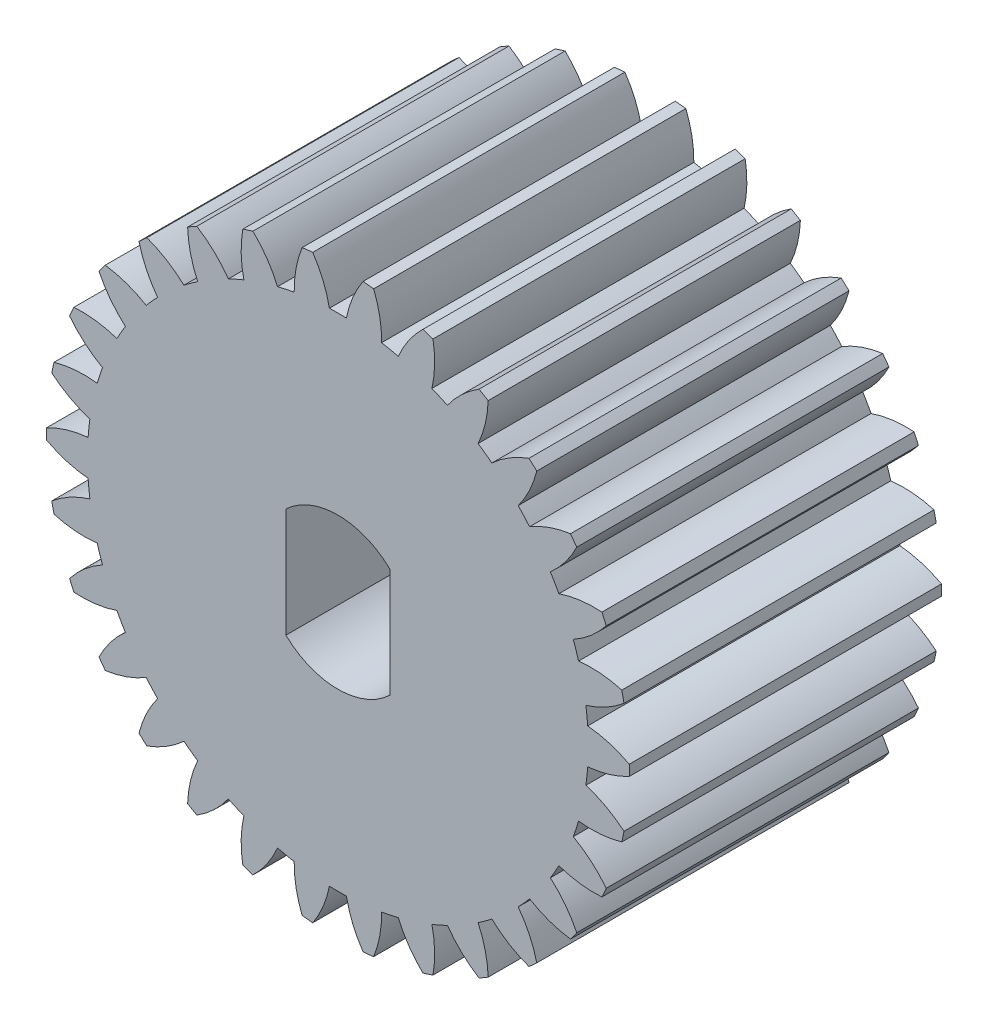
SolidWorks part; units mm, degrees
material "ABS"
ref_plane "Alzado" through (0, 0, 0) normal (0, 0, 1) x (1, 0, 0)
ref_plane "Planta" through (0, 0, 0) normal (0, 1, 0) x (1, 0, 0)
ref_plane "Vista lateral" through (0, 0, 0) normal (1, 0, 0) x (0, 0, -1)
sketch "Croquis1" plane through (0, 0, 0) normal (0, 0, 1) x (1, 0, 0)
  line L0 (-162.0016, 37.1002) -> (-162.0016, 32.9002)
  line L3 (-160.0016, 35.0002) -> (-160.0016, 39.913) construction
  line L4 (-158.0016, 37.1002) -> (-158.0016, 32.9002)
  arc A122 (-171.1997, 34.7961) -> (-169.6015, 34.3201) centre (-169.2256, 38.5032) ccw
  arc A123 (-169.6015, 34.3201) -> (-169.5331, 33.6695) centre (-160.0016, 35.0002) ccw
  arc A124 (-169.5331, 33.6695) -> (-170.9974, 32.8716) centre (-168.2957, 29.656) ccw
  arc A125 (-170.9974, 32.8716) -> (-170.9126, 32.4723) centre (-160.0016, 35.0002) ccw
  arc A126 (-170.9126, 32.4723) -> (-169.2503, 32.339) centre (-169.7523, 36.5089) ccw
  arc A127 (-169.2503, 32.339) -> (-169.0482, 31.7169) centre (-160.0016, 35.0002) ccw
  arc A128 (-169.0482, 31.7169) -> (-170.3146, 30.632) centre (-167.0033, 28.0483) ccw
  arc A129 (-170.3146, 30.632) -> (-170.1486, 30.2591) centre (-160.0016, 35.0002) ccw
  arc A130 (-170.1486, 30.2591) -> (-168.4949, 30.4742) centre (-169.8529, 34.4486) ccw
  arc A131 (-168.4949, 30.4742) -> (-168.1679, 29.9077) centre (-160.0016, 35.0002) ccw
  arc A132 (-168.1679, 29.9077) -> (-169.181, 28.5832) centre (-165.4049, 26.7445) ccw
  arc A133 (-169.181, 28.5832) -> (-168.9411, 28.253) centre (-160.0016, 35.0002) ccw
  arc A134 (-168.9411, 28.253) -> (-167.3683, 28.8073) centre (-169.523, 32.4125) ccw
  arc A135 (-167.3683, 28.8073) -> (-166.9306, 28.3212) centre (-160.0016, 35.0002) ccw
  arc A136 (-166.9306, 28.3212) -> (-167.6463, 26.815) centre (-163.5704, 25.8015) ccw
  arc A137 (-167.6463, 26.815) -> (-167.3429, 26.5418) centre (-160.0016, 35.0002) ccw
  arc A138 (-167.3429, 26.5418) -> (-165.9197, 27.411) centre (-168.7769, 30.4894) ccw
  arc A139 (-165.9197, 27.411) -> (-165.3905, 27.0265) centre (-160.0016, 35.0002) ccw
  arc A140 (-165.3905, 27.0265) -> (-165.7774, 25.4044) centre (-161.5799, 25.2605) ccw
  arc A141 (-165.7774, 25.4044) -> (-165.4239, 25.2003) centre (-160.0016, 35.0002) ccw
  arc A142 (-165.4239, 25.2003) -> (-164.2125, 26.3464) centre (-167.6473, 28.7635) ccw
  arc A143 (-164.2125, 26.3464) -> (-163.615, 26.0803) centre (-160.0016, 35.0002) ccw
  arc A144 (-163.615, 26.0803) -> (-163.6561, 24.4132) centre (-159.5204, 25.1452) ccw
  arc A145 (-163.6561, 24.4132) -> (-163.2679, 24.2871) centre (-160.0016, 35.0002) ccw
  arc A146 (-163.2679, 24.2871) -> (-162.3213, 25.66) centre (-166.1835, 27.3102) ccw
  arc A147 (-162.3213, 25.66) -> (-161.6814, 25.524) centre (-160.0016, 35.0002) ccw
  arc A148 (-161.6814, 25.524) -> (-161.3751, 23.8848) centre (-157.4819, 25.4606) ccw
  arc A149 (-161.3751, 23.8848) -> (-160.9691, 23.8421) centre (-160.0016, 35.0002) ccw
  arc A150 (-160.9691, 23.8421) -> (-160.3286, 25.3818) centre (-164.4496, 26.1929) ccw
  arc A151 (-160.3286, 25.3818) -> (-159.6745, 25.3818) centre (-160.0016, 35.0002) ccw
  arc A152 (-159.6745, 25.3818) -> (-159.034, 23.8421) centre (-155.5536, 26.1929) ccw
  arc A153 (-159.034, 23.8421) -> (-158.6281, 23.8848) centre (-160.0016, 35.0002) ccw
  arc A154 (-158.6281, 23.8848) -> (-158.3217, 25.524) centre (-162.5212, 25.4606) ccw
  arc A155 (-158.3217, 25.524) -> (-157.6819, 25.66) centre (-160.0016, 35.0002) ccw
  arc A156 (-157.6819, 25.66) -> (-156.7353, 24.2871) centre (-153.8196, 27.3102) ccw
  arc A157 (-156.7353, 24.2871) -> (-156.347, 24.4132) centre (-160.0016, 35.0002) ccw
  arc A158 (-156.347, 24.4132) -> (-156.3882, 26.0803) centre (-160.4828, 25.1452) ccw
  arc A159 (-156.3882, 26.0803) -> (-155.7906, 26.3464) centre (-160.0016, 35.0002) ccw
  arc A160 (-155.7906, 26.3464) -> (-154.5793, 25.2003) centre (-152.3559, 28.7635) ccw
  arc A161 (-154.5793, 25.2003) -> (-154.2257, 25.4044) centre (-160.0016, 35.0002) ccw
  arc A162 (-154.2257, 25.4044) -> (-154.6126, 27.0265) centre (-158.4233, 25.2605) ccw
  arc A163 (-154.6126, 27.0265) -> (-154.0834, 27.411) centre (-160.0016, 35.0002) ccw
  arc A164 (-154.0834, 27.411) -> (-152.6602, 26.5418) centre (-151.2263, 30.4894) ccw
  arc A165 (-152.6602, 26.5418) -> (-152.3569, 26.815) centre (-160.0016, 35.0002) ccw
  arc A166 (-152.3569, 26.815) -> (-153.0725, 28.3212) centre (-156.4328, 25.8015) ccw
  arc A167 (-153.0725, 28.3212) -> (-152.6348, 28.8073) centre (-160.0016, 35.0002) ccw
  arc A168 (-152.6348, 28.8073) -> (-151.0621, 28.253) centre (-150.4802, 32.4125) ccw
  arc A169 (-151.0621, 28.253) -> (-150.8221, 28.5832) centre (-160.0016, 35.0002) ccw
  arc A170 (-150.8221, 28.5832) -> (-151.8353, 29.9077) centre (-154.5982, 26.7445) ccw
  arc A171 (-151.8353, 29.9077) -> (-151.5082, 30.4742) centre (-160.0016, 35.0002) ccw
  arc A172 (-151.5082, 30.4742) -> (-149.8546, 30.2591) centre (-150.1502, 34.4486) ccw
  arc A173 (-149.8546, 30.2591) -> (-149.6885, 30.632) centre (-160.0016, 35.0002) ccw
  arc A174 (-149.6885, 30.632) -> (-150.955, 31.7169) centre (-152.9998, 28.0483) ccw
  arc A175 (-150.955, 31.7169) -> (-150.7528, 32.339) centre (-160.0016, 35.0002) ccw
  arc A176 (-150.7528, 32.339) -> (-149.0906, 32.4723) centre (-150.2508, 36.5089) ccw
  arc A177 (-149.0906, 32.4723) -> (-149.0057, 32.8716) centre (-160.0016, 35.0002) ccw
  arc A178 (-149.0057, 32.8716) -> (-150.47, 33.6695) centre (-151.7075, 29.656) ccw
  arc A179 (-150.47, 33.6695) -> (-150.4016, 34.3201) centre (-160.0016, 35.0002) ccw
  arc A180 (-150.4016, 34.3201) -> (-148.8034, 34.7961) centre (-150.7776, 38.5032) ccw
  arc A181 (-148.8034, 34.7961) -> (-148.8034, 35.2043) centre (-160.0016, 35.0002) ccw
  arc A182 (-148.8034, 35.2043) -> (-150.4016, 35.6803) centre (-150.7776, 31.4972) ccw
  arc A183 (-150.4016, 35.6803) -> (-150.47, 36.3309) centre (-160.0016, 35.0002) ccw
  arc A184 (-150.47, 36.3309) -> (-149.0057, 37.1288) centre (-151.7075, 40.3445) ccw
  arc A185 (-149.0057, 37.1288) -> (-149.0906, 37.5281) centre (-160.0016, 35.0002) ccw
  arc A186 (-149.0906, 37.5281) -> (-150.7528, 37.6614) centre (-150.2508, 33.4915) ccw
  arc A187 (-150.7528, 37.6614) -> (-150.955, 38.2835) centre (-160.0016, 35.0002) ccw
  arc A188 (-150.955, 38.2835) -> (-149.6885, 39.3684) centre (-152.9998, 41.9521) ccw
  arc A189 (-149.6885, 39.3684) -> (-149.8546, 39.7414) centre (-160.0016, 35.0002) ccw
  arc A190 (-149.8546, 39.7414) -> (-151.5082, 39.5262) centre (-150.1502, 35.5518) ccw
  arc A191 (-151.5082, 39.5262) -> (-151.8353, 40.0927) centre (-160.0016, 35.0002) ccw
  arc A192 (-151.8353, 40.0927) -> (-150.8221, 41.4172) centre (-154.5982, 43.2559) ccw
  arc A193 (-150.8221, 41.4172) -> (-151.0621, 41.7474) centre (-160.0016, 35.0002) ccw
  arc A194 (-151.0621, 41.7474) -> (-152.6348, 41.1932) centre (-150.4802, 37.5879) ccw
  arc A195 (-152.6348, 41.1932) -> (-153.0725, 41.6793) centre (-160.0016, 35.0002) ccw
  arc A196 (-153.0725, 41.6793) -> (-152.3569, 43.1855) centre (-156.4328, 44.199) ccw
  arc A197 (-152.3569, 43.1855) -> (-152.6602, 43.4586) centre (-160.0016, 35.0002) ccw
  arc A198 (-152.6602, 43.4586) -> (-154.0834, 42.5895) centre (-151.2263, 39.511) ccw
  arc A199 (-154.0834, 42.5895) -> (-154.6126, 42.9739) centre (-160.0016, 35.0002) ccw
  arc A200 (-154.6126, 42.9739) -> (-154.2257, 44.596) centre (-158.4233, 44.7399) ccw
  arc A201 (-154.2257, 44.596) -> (-154.5793, 44.8001) centre (-160.0016, 35.0002) ccw
  arc A202 (-154.5793, 44.8001) -> (-155.7906, 43.6541) centre (-152.3559, 41.2369) ccw
  arc A203 (-155.7906, 43.6541) -> (-156.3882, 43.9201) centre (-160.0016, 35.0002) ccw
  arc A204 (-156.3882, 43.9201) -> (-156.347, 45.5872) centre (-160.4828, 44.8552) ccw
  arc A205 (-156.347, 45.5872) -> (-156.7353, 45.7134) centre (-160.0016, 35.0002) ccw
  arc A206 (-156.7353, 45.7134) -> (-157.6819, 44.3405) centre (-153.8196, 42.6903) ccw
  arc A207 (-157.6819, 44.3405) -> (-158.3217, 44.4765) centre (-160.0016, 35.0002) ccw
  arc A208 (-158.3217, 44.4765) -> (-158.6281, 46.1157) centre (-162.5212, 44.5398) ccw
  arc A209 (-158.6281, 46.1157) -> (-159.034, 46.1583) centre (-160.0016, 35.0002) ccw
  arc A210 (-159.034, 46.1583) -> (-159.6745, 44.6187) centre (-155.5536, 43.8075) ccw
  arc A211 (-159.6745, 44.6187) -> (-160.3286, 44.6187) centre (-160.0016, 35.0002) ccw
  arc A212 (-160.3286, 44.6187) -> (-160.9691, 46.1583) centre (-164.4496, 43.8075) ccw
  arc A213 (-160.9691, 46.1583) -> (-161.3751, 46.1157) centre (-160.0016, 35.0002) ccw
  arc A214 (-161.3751, 46.1157) -> (-161.6814, 44.4765) centre (-157.4819, 44.5398) ccw
  arc A215 (-161.6814, 44.4765) -> (-162.3213, 44.3405) centre (-160.0016, 35.0002) ccw
  arc A216 (-162.3213, 44.3405) -> (-163.2679, 45.7134) centre (-166.1835, 42.6903) ccw
  arc A217 (-163.2679, 45.7134) -> (-163.6561, 45.5872) centre (-160.0016, 35.0002) ccw
  arc A218 (-163.6561, 45.5872) -> (-163.615, 43.9201) centre (-159.5204, 44.8552) ccw
  arc A219 (-163.615, 43.9201) -> (-164.2125, 43.6541) centre (-160.0016, 35.0002) ccw
  arc A220 (-164.2125, 43.6541) -> (-165.4239, 44.8001) centre (-167.6473, 41.2369) ccw
  arc A221 (-165.4239, 44.8001) -> (-165.7774, 44.596) centre (-160.0016, 35.0002) ccw
  arc A222 (-165.7774, 44.596) -> (-165.3905, 42.9739) centre (-161.5799, 44.7399) ccw
  arc A223 (-165.3905, 42.9739) -> (-165.9197, 42.5895) centre (-160.0016, 35.0002) ccw
  arc A224 (-165.9197, 42.5895) -> (-167.3429, 43.4586) centre (-168.7769, 39.511) ccw
  arc A225 (-167.3429, 43.4586) -> (-167.6463, 43.1855) centre (-160.0016, 35.0002) ccw
  arc A226 (-167.6463, 43.1855) -> (-166.9306, 41.6793) centre (-163.5704, 44.199) ccw
  arc A227 (-166.9306, 41.6793) -> (-167.3683, 41.1932) centre (-160.0016, 35.0002) ccw
  arc A228 (-167.3683, 41.1932) -> (-168.9411, 41.7474) centre (-169.523, 37.5879) ccw
  arc A229 (-168.9411, 41.7474) -> (-169.181, 41.4172) centre (-160.0016, 35.0002) ccw
  arc A230 (-169.181, 41.4172) -> (-168.1679, 40.0927) centre (-165.4049, 43.2559) ccw
  arc A231 (-168.1679, 40.0927) -> (-168.4949, 39.5262) centre (-160.0016, 35.0002) ccw
  arc A232 (-168.4949, 39.5262) -> (-170.1486, 39.7414) centre (-169.8529, 35.5518) ccw
  arc A233 (-170.1486, 39.7414) -> (-170.3146, 39.3684) centre (-160.0016, 35.0002) ccw
  arc A234 (-170.3146, 39.3684) -> (-169.0482, 38.2835) centre (-167.0033, 41.9521) ccw
  arc A235 (-169.0482, 38.2835) -> (-169.2503, 37.6614) centre (-160.0016, 35.0002) ccw
  arc A236 (-169.2503, 37.6614) -> (-170.9126, 37.5281) centre (-169.7523, 33.4915) ccw
  arc A237 (-170.9126, 37.5281) -> (-170.9974, 37.1288) centre (-160.0016, 35.0002) ccw
  arc A238 (-170.9974, 37.1288) -> (-169.5331, 36.3309) centre (-168.2957, 40.3445) ccw
  arc A239 (-169.5331, 36.3309) -> (-169.6015, 35.6803) centre (-160.0016, 35.0002) ccw
  arc A240 (-169.6015, 35.6803) -> (-171.1997, 35.2043) centre (-169.2256, 31.4972) ccw
  arc A241 (-171.1997, 35.2043) -> (-171.1997, 34.7961) centre (-160.0016, 35.0002) ccw
  arc A242 (-162.0016, 32.9002) -> (-158.0016, 32.9002) centre (-160.0016, 35.0002) ccw
  arc A243 (-158.0016, 37.1002) -> (-162.0016, 37.1002) centre (-160.0016, 35.0002) ccw
  dimension "D1" = 11.2
  dimension "D2" = 9.624
  dimension "D4" = 5.8
  dimension "D3" = 0.4082
  dimension "D5" = 2
extrude "Saliente-Extruir1" add sketch "Croquis1" along normal blind 12
sketch "Croquis2" plane through (0, 0, 12) normal (0, 0, 1) x (1, 0, 0)
  circle A0 centre (-160.0016, 35.0002) radius 9.624
